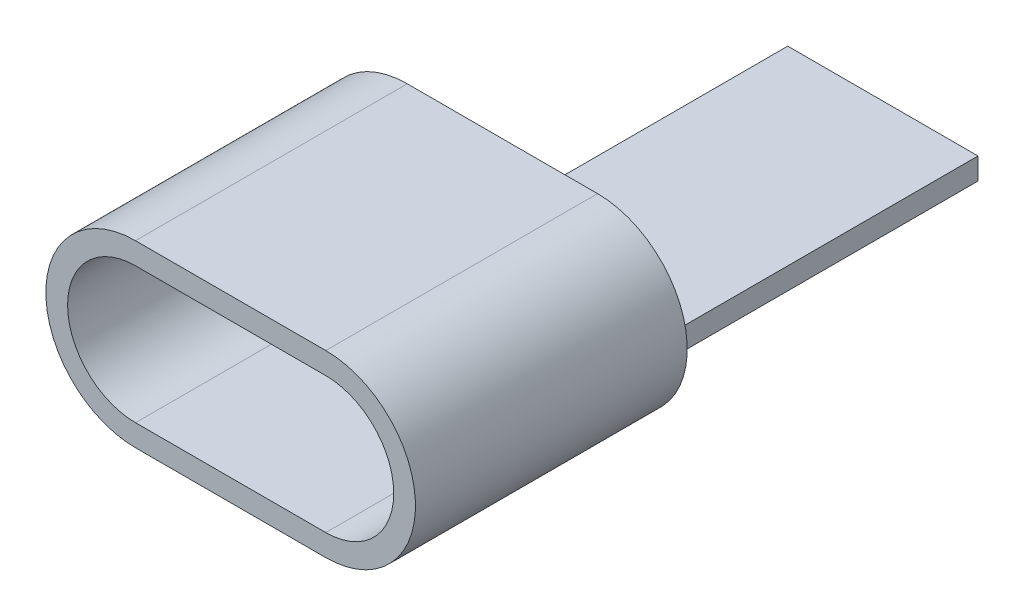
SolidWorks part; units mm, degrees
ref_plane "Front Plane" through (0, 0, 0) normal (0, 0, 1) x (1, 0, 0)
ref_plane "Top Plane" through (0, 0, 0) normal (0, 1, 0) x (1, 0, 0)
ref_plane "Right Plane" through (0, 0, 0) normal (1, 0, 0) x (0, 0, -1)
sketch "Sketch1" plane through (0, 0, 0) normal (0, 1, 0) x (1, 0, 0)
  line L0 (-55, 0) -> (55, 0) construction
  line L1 (-7, 0) -> (7, 0)
  line L2 (-7, 0) -> (-7, 28)
  line L3 (-7, 28) -> (7, 28)
  line L4 (7, 0) -> (7, 28)
  line L5 (0, -55) -> (0, 55) construction
  point P6 (0, 28)
  dimension "D1" = 28
  dimension "D2" = 14
extrude "Boss-Extrude1" add sketch "Sketch1" along normal blind 1.6
sketch "Sketch2" plane through (0, 0, 0) normal (0, 0, 1) x (1, 0, 0)
  line L0 (-7, 6.6) -> (7, 6.6) construction
  line L1 (-7, 11.6) -> (7, 11.6)
  line L2 (-7, 1.6) -> (7, 1.6)
  line L3 (-7, 13.2) -> (7, 13.2)
  line L4 (-7, 0) -> (7, 0)
  line L7 (-7, 0) -> (7, 0)
  line L8 (7, 0) -> (7, 1.6)
  line L9 (7, 1.6) -> (-7, 1.6)
  line L10 (-7, 1.6) -> (-7, 0)
  line L11 (-7, 0) -> (7, 0)
  line L12 (7, 0) -> (7, 1.6)
  line L13 (7, 1.6) -> (-7, 1.6)
  line L14 (-7, 1.6) -> (-7, 0)
  arc A0 (-7, 11.6) -> (-7, 1.6) centre (-7, 6.6) ccw
  arc A1 (7, 1.6) -> (7, 11.6) centre (7, 6.6) ccw
  arc A2 (7, 0) -> (7, 13.2) centre (7, 6.6) ccw
  arc A3 (-7, 13.2) -> (-7, 0) centre (-7, 6.6) ccw
  point P2 (0, 6.6)
  point P9 (0, 0)
  point P11 (0, 0)
  point P13 (0, 0)
  dimension "D1" = 5
  dimension "D2" = 0
  dimension "D3" = 1.6
extrude "Boss-Extrude2" add sketch "Sketch2" along normal blind 20 contours L3 A3 L14 A0 L1 A1 L12 A2 | L2 L14 L4 L12
